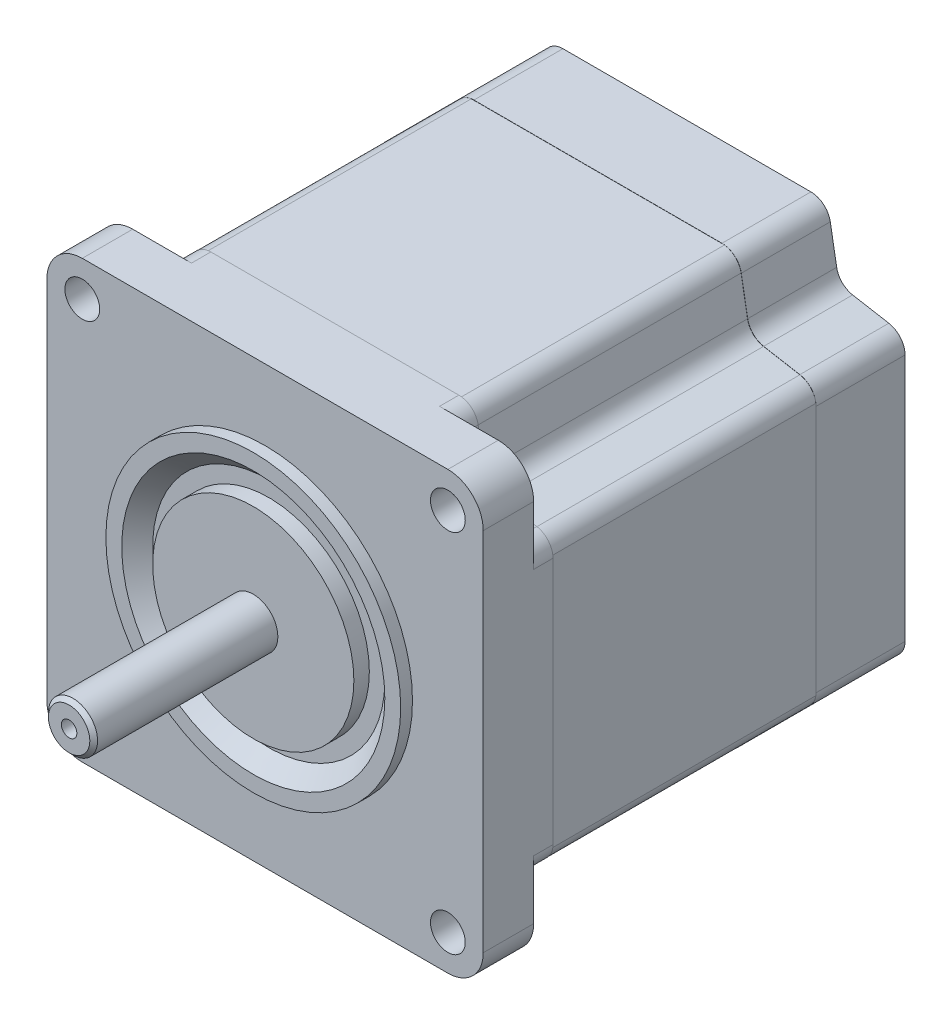
SolidWorks part; units mm, degrees
ref_plane "Front" through (0, 0, 0) normal (0, 0, 1) x (1, 0, 0)
ref_plane "Top" through (0, 0, 0) normal (0, 1, 0) x (1, 0, 0)
ref_plane "Right" through (0, 0, 0) normal (1, 0, 0) x (0, 0, -1)
sketch "Sketch1" plane through (0, 0, 0) normal (0, 0, 1) x (1, 0, 0)
  line L1 (-4.572, 0) -> (-51.816, 0)
  line L2 (0, 4.572) -> (0, 51.816)
  line L3 (-4.572, 56.388) -> (-51.816, 56.388)
  line L4 (-56.388, 4.572) -> (-56.388, 51.816)
  line L7 (-51.816, 51.816) -> (-4.572, 51.816) construction
  line L8 (-51.816, 51.816) -> (-51.816, 4.572) construction
  line L9 (-51.816, 4.572) -> (-4.572, 4.572) construction
  line L10 (-4.572, 51.816) -> (-4.572, 4.572) construction
  circle A0 centre (-4.572, 51.816) radius 2.2479
  circle A1 centre (-4.572, 4.572) radius 2.2479
  circle A2 centre (-51.816, 4.572) radius 2.2479
  circle A3 centre (-51.816, 51.816) radius 2.2479
  arc A4 (-51.816, 56.388) -> (-56.388, 51.816) centre (-51.816, 51.816) ccw
  arc A5 (-51.816, 0) -> (-56.388, 4.572) centre (-51.816, 4.572) cw
  arc A6 (-4.572, 0) -> (0, 4.572) centre (-4.572, 4.572) ccw
  arc A7 (0, 51.816) -> (-4.572, 56.388) centre (-4.572, 51.816) ccw
  point P16 (-56.388, 0)
  point P19 (0, 0)
  point P22 (0, 56.388)
  dimension "D6" = 4.4958
  dimension "D7" = 4.572
  dimension "D1" = 56.388
  dimension "D2" = 56.388
  dimension "D3" = 4.572
  dimension "D4" = 4.572
  dimension "D5" = 47.244
extrude "Extrude1" add sketch "Sketch1" against normal blind 9.017
sketch "Sketch2" plane through (0, 0, 0) normal (0, 0, 1) x (1, 0, 0)
  line L0 (-28.194, 28.194) -> (-28.194, 56.388) construction
  line L1 (-4.572, 56.388) -> (-51.816, 56.388) construction
  line L2 (-28.194, 28.194) -> (0, 28.194) construction
  line L3 (0, 4.572) -> (0, 51.816) construction
  circle A0 centre (-28.194, 28.194) radius 19.05
  dimension "D1" = 38.1
extrude "Extrude2" add sketch "Sketch2" along normal blind 1.524
sketch "Sketch3" plane through (0, 0, 1.524) normal (0, 0, 1) x (1, 0, 0)
  line L0 (0, 4.572) -> (0, 51.816) construction
  line L1 (-4.572, 56.388) -> (-51.816, 56.388) construction
  line L2 (0, 4.572) -> (0, 51.816) construction
  line L3 (-4.572, 56.388) -> (-51.816, 56.388) construction
  line L4 (-28.194, 56.388) -> (-28.194, 28.194) construction
  line L5 (-28.194, 28.194) -> (0, 28.194) construction
  circle A0 centre (-28.194, 28.194) radius 3.175
  dimension "D1" = 6.35
extrude "Extrude3" add sketch "Sketch3" along normal blind 23.8
sketch "Sketch5" plane through (0, 0, -9.017) normal (0, 0, -1) x (-1, 0, 0)
  line L25 (4.572, 0.0254) -> (51.816, 0.0254)
  line L26 (56.3626, 4.572) -> (56.3626, 51.816)
  line L27 (51.816, 56.3626) -> (4.572, 56.3626)
  line L28 (0.0254, 51.816) -> (0.0254, 4.572)
  line L29 (4.572, 0.0254) -> (51.816, 0.0254)
  line L30 (56.3626, 4.572) -> (56.3626, 51.816)
  line L31 (51.816, 56.3626) -> (4.572, 56.3626)
  line L32 (0.0254, 51.816) -> (0.0254, 4.572)
  arc A20 (0.0254, 4.572) -> (4.572, 0.0254) centre (4.572, 4.572) ccw
  arc A21 (51.816, 0.0254) -> (56.3626, 4.572) centre (51.816, 4.572) ccw
  arc A22 (56.3626, 51.816) -> (51.816, 56.3626) centre (51.816, 51.816) ccw
  arc A23 (4.572, 56.3626) -> (0.0254, 51.816) centre (4.572, 51.816) ccw
  arc A24 (0.0254, 4.572) -> (4.572, 0.0254) centre (4.572, 4.572) ccw
  arc A25 (51.816, 0.0254) -> (56.3626, 4.572) centre (51.816, 4.572) ccw
  arc A26 (56.3626, 51.816) -> (51.816, 56.3626) centre (51.816, 51.816) ccw
  arc A27 (4.572, 56.3626) -> (0.0254, 51.816) centre (4.572, 51.816) ccw
  dimension "D1" = 0.0254
extrude "Extrude5" add sketch "Sketch5" along normal blind 34
sketch "Sketch6" plane through (0, 0, -43.017) normal (0, 0, -1) x (-1, 0, 0)
  line L20 (0, 51.816) -> (0, 4.572)
  line L21 (4.572, 0) -> (51.816, 0)
  line L22 (56.388, 4.572) -> (56.388, 51.816)
  line L23 (51.816, 56.388) -> (4.572, 56.388)
  line L24 (0, 51.816) -> (0, 4.572)
  line L25 (4.572, 0) -> (51.816, 0)
  line L26 (56.388, 4.572) -> (56.388, 51.816)
  line L27 (51.816, 56.388) -> (4.572, 56.388)
  arc A24 (0, 4.572) -> (4.572, 0) centre (4.572, 4.572) ccw
  arc A25 (51.816, 0) -> (56.388, 4.572) centre (51.816, 4.572) ccw
  arc A26 (56.388, 51.816) -> (51.816, 56.388) centre (51.816, 51.816) ccw
  arc A27 (4.572, 56.388) -> (0, 51.816) centre (4.572, 51.816) ccw
  arc A28 (0, 4.572) -> (4.572, 0) centre (4.572, 4.572) ccw
  arc A29 (51.816, 0) -> (56.388, 4.572) centre (51.816, 4.572) ccw
  arc A30 (56.388, 51.816) -> (51.816, 56.388) centre (51.816, 51.816) ccw
  arc A31 (4.572, 56.388) -> (0, 51.816) centre (4.572, 51.816) ccw
  dimension "D1" = 0.0254
sketch "Sketch7" plane through (0, 0, -43.017) normal (0, 0, -1) x (-1, 0, 0)
  line L0 (2.0989, 46.6974) -> (6.8011, 47.5265)
  line L1 (8.8615, 49.5869) -> (9.6906, 54.2891)
  line L2 (51.816, 56.388) -> (4.572, 56.388) construction
  line L3 (0, 51.816) -> (0, 4.572) construction
  line L4 (12.192, 56.388) -> (4.572, 56.388)
  line L5 (0, 51.816) -> (0, 44.196)
  line L6 (28.194, 56.388) -> (28.194, 28.194) construction
  line L7 (0, 28.194) -> (28.194, 28.194) construction
  line L8 (56.388, 51.816) -> (56.388, 44.196)
  line L9 (44.196, 56.388) -> (51.816, 56.388)
  line L10 (47.5265, 49.5869) -> (46.6974, 54.2891)
  line L11 (54.2891, 46.6974) -> (49.5869, 47.5265)
  line L12 (54.2891, 9.6906) -> (49.5869, 8.8615)
  line L13 (47.5265, 6.8011) -> (46.6974, 2.0989)
  line L14 (44.196, 0) -> (51.816, 0)
  line L15 (56.388, 4.572) -> (56.388, 12.192)
  line L16 (0, 4.572) -> (0, 12.192)
  line L17 (12.192, 0) -> (4.572, 0)
  line L18 (8.8615, 6.8011) -> (9.6906, 2.0989)
  line L19 (2.0989, 9.6906) -> (6.8011, 8.8615)
  arc A0 (0, 44.196) -> (2.0989, 46.6974) centre (2.54, 44.196) cw
  arc A1 (8.8615, 49.5869) -> (6.8011, 47.5265) centre (6.3601, 50.0279) cw
  arc A2 (9.6906, 54.2891) -> (12.192, 56.388) centre (12.192, 53.848) cw
  arc A3 (4.572, 56.388) -> (0, 51.816) centre (4.572, 51.816) ccw construction
  arc A4 (4.572, 56.388) -> (0, 51.816) centre (4.572, 51.816) ccw
  arc A5 (51.816, 56.388) -> (56.388, 51.816) centre (51.816, 51.816) cw
  arc A6 (46.6974, 54.2891) -> (44.196, 56.388) centre (44.196, 53.848) ccw
  arc A7 (47.5265, 49.5869) -> (49.5869, 47.5265) centre (50.0279, 50.0279) ccw
  arc A8 (56.388, 44.196) -> (54.2891, 46.6974) centre (53.848, 44.196) ccw
  arc A9 (56.388, 12.192) -> (54.2891, 9.6906) centre (53.848, 12.192) cw
  arc A10 (47.5265, 6.8011) -> (49.5869, 8.8615) centre (50.0279, 6.3601) cw
  arc A11 (46.6974, 2.0989) -> (44.196, 0) centre (44.196, 2.54) cw
  arc A12 (51.816, 0) -> (56.388, 4.572) centre (51.816, 4.572) ccw
  arc A13 (4.572, 0) -> (0, 4.572) centre (4.572, 4.572) cw
  arc A14 (9.6906, 2.0989) -> (12.192, 0) centre (12.192, 2.54) ccw
  arc A15 (8.8615, 6.8011) -> (6.8011, 8.8615) centre (6.3601, 6.3601) ccw
  arc A16 (0, 12.192) -> (2.0989, 9.6906) centre (2.54, 12.192) ccw
  dimension "D1" = 2.54
  dimension "D2" = 12.192
  dimension "D3" = 100
extrude "Cut-Extrude2" cut sketch "Sketch7" against normal blind 34
extrude "Extrude7" add sketch "Sketch6" along normal blind 11.5
sketch "Sketch8" plane through (0, 0, -54.517) normal (0, 0, -1) x (-1, 0, 0)
  line L0 (2.0989, 46.7228) -> (6.7795, 47.5481)
  line L1 (8.8399, 49.6085) -> (9.6652, 54.2891)
  line L2 (51.816, 56.388) -> (4.572, 56.388) construction
  line L3 (0, 51.816) -> (0, 4.572) construction
  line L4 (4.572, 56.388) -> (12.1666, 56.388)
  line L5 (0, 51.816) -> (0, 44.2214)
  line L6 (28.194, 56.388) -> (28.194, 21.986) construction
  line L7 (0, 28.194) -> (33.0214, 28.194) construction
  line L8 (56.388, 51.816) -> (56.388, 44.2214)
  line L9 (51.816, 56.388) -> (44.2214, 56.388)
  line L10 (47.5481, 49.6085) -> (46.7228, 54.2891)
  line L11 (54.2891, 46.7228) -> (49.6085, 47.5481)
  line L12 (54.2891, 9.6652) -> (49.6085, 8.8399)
  line L13 (47.5481, 6.7795) -> (46.7228, 2.0989)
  line L14 (51.816, 0) -> (44.2214, 0)
  line L15 (56.388, 4.572) -> (56.388, 12.1666)
  line L16 (0, 4.572) -> (0, 12.1666)
  line L17 (4.572, 0) -> (12.1666, 0)
  line L18 (8.8399, 6.7795) -> (9.6652, 2.0989)
  line L19 (2.0989, 9.6652) -> (6.7795, 8.8399)
  arc A0 (0, 44.2214) -> (2.0989, 46.7228) centre (2.54, 44.2214) cw
  arc A1 (8.8399, 49.6085) -> (6.7795, 47.5481) centre (6.3385, 50.0495) cw
  arc A2 (9.6652, 54.2891) -> (12.1666, 56.388) centre (12.1666, 53.848) cw
  arc A3 (4.572, 56.388) -> (0, 51.816) centre (4.572, 51.816) ccw construction
  arc A4 (4.572, 56.388) -> (0, 51.816) centre (4.572, 51.816) ccw
  arc A5 (51.816, 56.388) -> (56.388, 51.816) centre (51.816, 51.816) cw
  arc A6 (46.7228, 54.2891) -> (44.2214, 56.388) centre (44.2214, 53.848) ccw
  arc A7 (47.5481, 49.6085) -> (49.6085, 47.5481) centre (50.0495, 50.0495) ccw
  arc A8 (56.388, 44.2214) -> (54.2891, 46.7228) centre (53.848, 44.2214) ccw
  arc A9 (56.388, 12.1666) -> (54.2891, 9.6652) centre (53.848, 12.1666) cw
  arc A10 (47.5481, 6.7795) -> (49.6085, 8.8399) centre (50.0495, 6.3385) cw
  arc A11 (46.7228, 2.0989) -> (44.2214, 0) centre (44.2214, 2.54) cw
  arc A12 (51.816, 0) -> (56.388, 4.572) centre (51.816, 4.572) ccw
  arc A13 (4.572, 0) -> (0, 4.572) centre (4.572, 4.572) cw
  arc A14 (9.6652, 2.0989) -> (12.1666, 0) centre (12.1666, 2.54) ccw
  arc A15 (8.8399, 6.7795) -> (6.7795, 8.8399) centre (6.3385, 6.3385) ccw
  arc A16 (0, 12.1666) -> (2.0989, 9.6652) centre (2.54, 12.1666) ccw
  dimension "D1" = 2.54
  dimension "D2" = 12.1666
  dimension "D3" = 100
extrude "Cut-Extrude3" cut sketch "Sketch8" against normal blind 48
sketch "Sketch9" plane through (0, 0, 0) normal (0, -1, 0) x (1, 0, 0)
  line L0 (-28.194, -54.517) -> (-28.194, -38.3423) construction
  line L1 (-12.1666, -54.517) -> (-44.2214, -54.517) construction
  line L2 (-38.444, -54.517) -> (-17.944, -54.517)
  line L3 (-38.444, -54.517) -> (-38.444, -43.017)
  line L4 (-38.444, -43.017) -> (-37.444, -43.017)
  line L5 (-17.944, -54.517) -> (-17.944, -43.017)
  line L6 (-37.444, -50.517) -> (-37.444, -43.017)
  line L7 (-18.944, -50.517) -> (-18.944, -43.017)
  line L8 (-37.444, -50.517) -> (-18.944, -50.517)
  line L9 (-18.944, -43.017) -> (-17.944, -43.017)
  line L10 (-37.444, -54.517) -> (-37.444, -43.017) construction
  line L11 (-38.444, -50.517) -> (-17.944, -50.517) construction
  line L12 (-18.944, -54.517) -> (-18.944, -43.017) construction
  dimension "D1" = 1
  dimension "D2" = 20.5
  dimension "D3" = 1
  dimension "D4" = 4
extrude "Extrude8" add sketch "Sketch9" along normal blind 5
chamfer "Chanfro1" distance 0.5 angle 45 1 edges at (-25.019, 28.194, 25.324)
sketch "Esboço1" plane through (0, 0, 25.324) normal (0, 0, 1) x (1, 0, 0)
  circle A0 centre (-28.194, 28.194) radius 1
extrude "Corte-extrusão1" cut sketch "Esboço1" against normal blind 2
ref_plane "Plano1" through (0, 28.194, 0) normal (0, 1, 0) x (-1, 0, 0)
sketch "Esboço2" plane through (0, 28.194, 0) normal (0, 1, 0) x (-1, 0, 0)
  line L0 (28.194, 25.324) -> (28.194, 0) construction
  line L1 (29.194, 25.324) -> (27.194, 25.324) construction
  line L2 (51.816, 0) -> (4.572, 0) construction
  line L3 (11.194, 1.524) -> (13.194, -0.476)
  line L4 (47.244, 1.524) -> (9.144, 1.524) construction
  line L5 (13.194, -0.476) -> (15.194, -0.476)
  line L6 (15.194, -0.476) -> (15.194, 1.524)
  line L7 (11.194, 1.524) -> (15.194, 1.524)
  dimension "D1" = 17
  dimension "D2" = 4
  dimension "D3" = 2
  dimension "D4" = 2
revolve "Corte-Revolução1" cut sketch "Esboço2" angle 360 about L0
